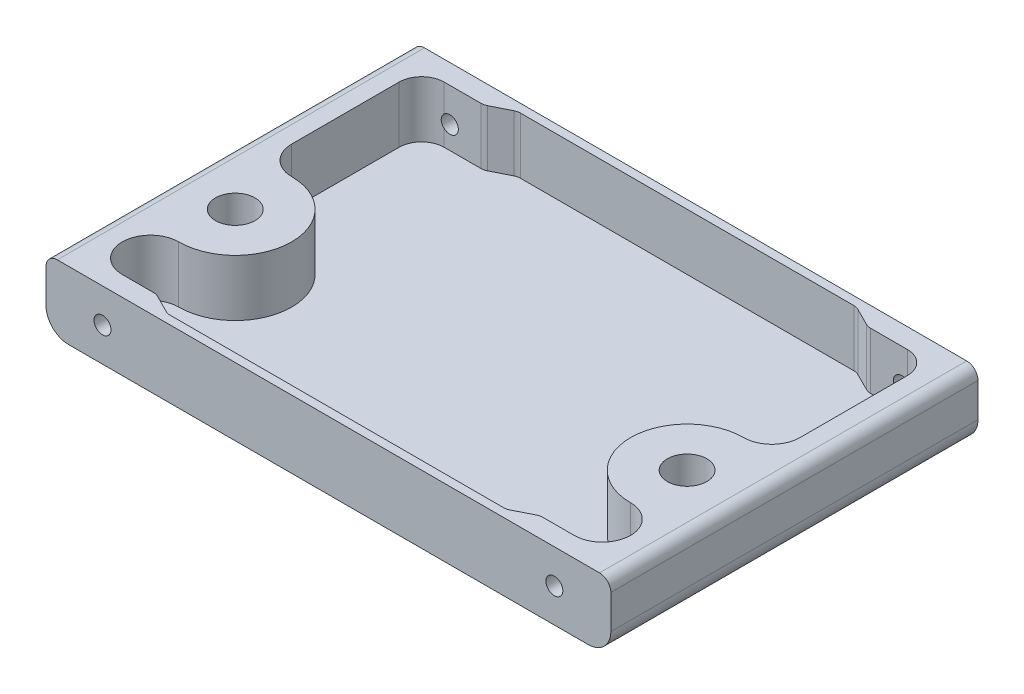
SolidWorks part; units mm, degrees
ref_plane "前视基准面" through (0, 0, 0) normal (0, 0, 1) x (1, 0, 0)
ref_plane "上视基准面" through (0, 0, 0) normal (0, 1, 0) x (1, 0, 0)
ref_plane "右视基准面" through (0, 0, 0) normal (1, 0, 0) x (0, 0, -1)
other "Configuration Table"
sketch "草图1" plane through (0, 0, 0) normal (0, 1, 0) x (1, 0, 0)
  line L1 (-50, -32.5) -> (50, -32.5)
  line L2 (-50, -32.5) -> (-50, 32.5)
  line L3 (-50, 32.5) -> (50, 32.5)
  line L4 (50, -32.5) -> (50, 32.5)
  line L5 (-50, -32.5) -> (50, 32.5) construction
  line L6 (-50, 32.5) -> (50, -32.5) construction
  point P0 (0, 0)
  dimension "D1" = 100
  dimension "D2" = 65
extrude "凸台-拉伸1" add sketch "草图1" along normal blind 12
sketch "草图2" plane through (0, 12, 0) normal (0, 1, 0) x (1, 0, 0)
  line L0 (0, -37.9045) -> (0, 37.9045) construction
  line L6 (-30.4223, 30.7889) -> (-33.5777, 29.2111)
  line L7 (-34.4721, 29) -> (-41, 29)
  line L8 (-29.5279, 31) -> (29.5279, 31)
  line L9 (-50, 32.5) -> (-50, -32.5) construction
  line L10 (-40, -52.6045) -> (-40, 4.7784) construction
  line L11 (-40, -29) -> (-34.4392, -29)
  line L12 (29.5239, -31) -> (-29.5239, -31)
  line L13 (-33.5382, -29.2145) -> (-30.425, -30.7855)
  line L14 (-50, -32.5) -> (50, -32.5) construction
  line L15 (-45, 6) -> (-45, 25)
  line L16 (-45, 49.1756) -> (-45, -43.1392) construction
  line L17 (-30, 31) -> (-30, -37.9045) construction
  line L18 (30, 31) -> (30, -37.9045) construction
  line L19 (45, 6) -> (45, 25)
  line L20 (33.5382, -29.2145) -> (30.425, -30.7855)
  line L21 (40, -29) -> (34.4392, -29)
  line L22 (34.4721, 29) -> (41, 29)
  line L23 (30.4223, 30.7889) -> (33.5777, 29.2111)
  arc A0 (-41, 29) -> (-45, 25) centre (-41, 25) ccw
  arc A1 (-29.5279, 31) -> (-30.4223, 30.7889) centre (-29.5279, 29) ccw
  arc A2 (-33.5777, 29.2111) -> (-34.4721, 29) centre (-34.4721, 31) cw
  circle A3 centre (-40, -9) radius 3.5
  arc A4 (-40, -19) -> (-40, 1) centre (-40, -9) ccw
  arc A5 (-40, -19) -> (-40, -29) centre (-40, -24) ccw
  arc A6 (-40, 1) -> (-45, 6) centre (-40, 6) cw
  arc A7 (-29.5239, -31) -> (-30.425, -30.7855) centre (-29.5239, -29) cw
  arc A8 (-34.4392, -29) -> (-33.5382, -29.2145) centre (-34.4392, -31) cw
  arc A9 (34.4392, -29) -> (33.5382, -29.2145) centre (34.4392, -31) ccw
  arc A10 (29.5239, -31) -> (30.425, -30.7855) centre (29.5239, -29) ccw
  arc A11 (40, 1) -> (45, 6) centre (40, 6) ccw
  arc A12 (40, -19) -> (40, -29) centre (40, -24) cw
  arc A13 (40, -19) -> (40, 1) centre (40, -9) cw
  circle A14 centre (40, -9) radius 3.5
  arc A15 (33.5777, 29.2111) -> (34.4721, 29) centre (34.4721, 31) ccw
  arc A16 (29.5279, 31) -> (30.4223, 30.7889) centre (29.5279, 29) cw
  arc A17 (41, 29) -> (45, 25) centre (41, 25) cw
  point P3 (0, 0)
  point P6 (30, -31)
  point P9 (-30, 31)
  point P11 (0, 31)
  point P18 (-34, 29)
  point P35 (0, 31)
  point P37 (-30, -31)
  point P40 (-30, -37.9045)
  point P69 (0, -31)
  point P70 (34, 29)
  point P71 (-128.5879, 7.5301)
  dimension "D5" = 4
  dimension "D2" = 2
  dimension "D4" = 7
  dimension "D10" = 2
  dimension "D13" = 5
  dimension "D1" = 30
  dimension "D3" = 23.5
  dimension "D6" = 7
  dimension "D7" = 3.5
  dimension "D8" = 10
  dimension "D9" = 30
  dimension "D11" = 62
  dimension "D12" = 1.5
extrude "切除-拉伸2" cut sketch "草图2" against normal blind 10 contours A9 L20 A10 L12 A7 L13 A8 L11 A5 A4 A6 L15 A0 L7 A2 L6 A1 L8 A16 L23 A15 L22 A17 L19 A11 A13 A12 L21 | A3 | A14
sketch "草图3" plane through (0, 2, 0) normal (0, 1, 0) x (1, 0, 0)
  circle A0 centre (-40, -9) radius 3.5
extrude "切除-拉伸3" cut sketch "草图3" against normal through all contours A0
sketch "草图4" plane through (0, 2, 0) normal (0, 1, 0) x (1, 0, 0)
  circle A0 centre (40, -9) radius 3.5
extrude "切除-拉伸4" cut sketch "草图4" against normal through all
sketch "草图5" plane through (0, 0, 32.5) normal (0, 0, 1) x (1, 0, 0)
  line L0 (50, 12) -> (50, 0) construction
  line L1 (-50, 0) -> (50, 0) construction
  line L2 (-50, 12) -> (-50, 0) construction
  circle A0 centre (-40, 6) radius 1.5
  circle A1 centre (40, 6) radius 1.5
  point P8 (42.7622, 7.3829)
  dimension "D1" = 3
  dimension "D2" = 3
  dimension "D3" = 10
  dimension "D4" = 6
  dimension "D5" = 6
  dimension "D6" = 10
extrude "切除-拉伸5" cut sketch "草图5" against normal up to next
sketch "草图6" plane through (0, 0, -32.5) normal (0, 0, -1) x (-1, 0, 0)
  line L0 (50, 12) -> (50, 0) construction
  line L1 (-50, 0) -> (50, 0) construction
  line L2 (-50, 12) -> (-50, 0) construction
  circle A0 centre (-40, 6) radius 1.5
  circle A1 centre (40, 6) radius 1.5
  point P8 (42.7139, 6.3306)
  dimension "D1" = 3
  dimension "D2" = 3
  dimension "D3" = 10
  dimension "D4" = 6
  dimension "D5" = 10
  dimension "D6" = 6
extrude "切除-拉伸6" cut sketch "草图6" against normal up to next
fillet "圆角3" radius 2 2 edges at (-50, 12, 0) (50, 12, 0)
fillet "圆角4" radius 4 2 edges at (-50, 0, 0) (50, 0, 0)
